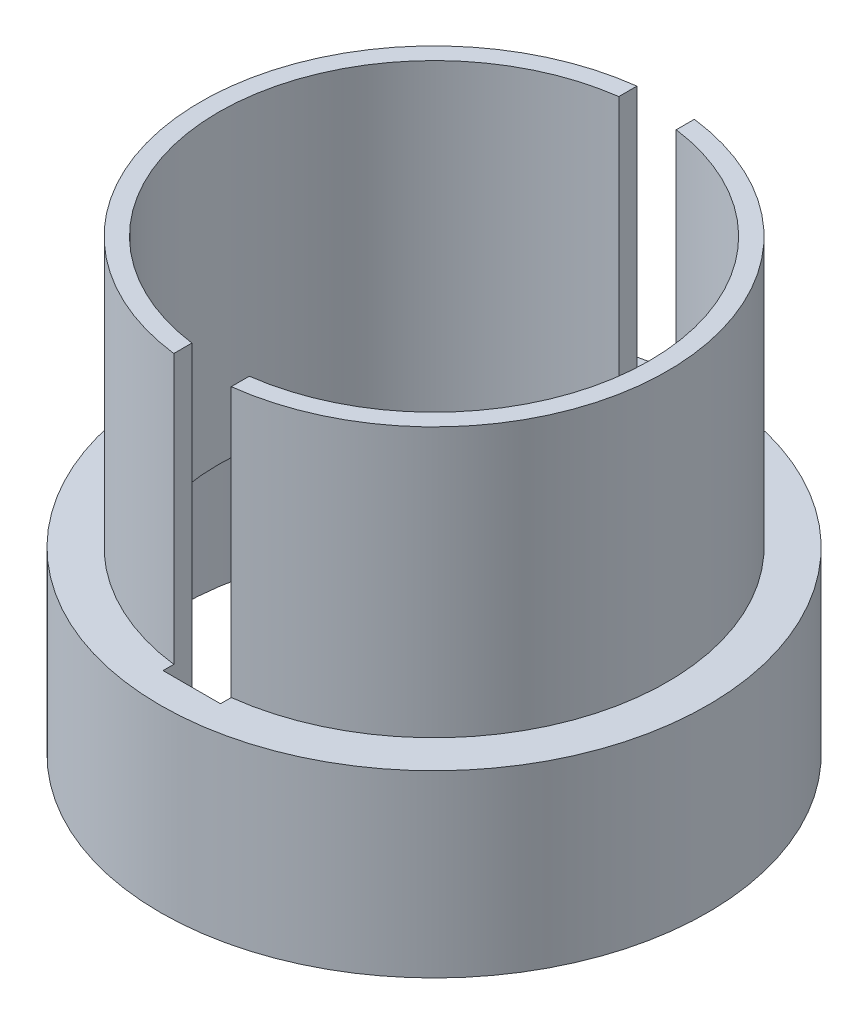
SolidWorks part; units mm, degrees
ref_plane "Front Plane" through (0, 0, 0) normal (0, 0, 1) x (1, 0, 0)
ref_plane "Top Plane" through (0, 0, 0) normal (0, 1, 0) x (1, 0, 0)
ref_plane "Right Plane" through (0, 0, 0) normal (1, 0, 0) x (0, 0, -1)
sketch "Sketch2" plane through (0, 0, 0) normal (0, 1, 0) x (1, 0, 0)
  circle A0 centre (0, 0) radius 15.25
  circle A1 centre (0, 0) radius 14.25
  dimension "D1" = 30.5
  dimension "D2" = 28.5
extrude "Boss-Extrude1" add sketch "Sketch2" along normal blind 10
sketch "Sketch4" plane through (0, 10, 0) normal (0, 1, 0) x (1, 0, 0)
  circle A0 centre (0, 0) radius 14.25
  dimension "D1" = 28.5
extrude "Boss-Extrude2" add sketch "Sketch4" against normal blind 2
sketch "Sketch5" plane through (0, 10, 0) normal (0, 1, 0) x (1, 0, 0)
  circle A0 centre (0, 0) radius 12
  dimension "D1" = 24
extrude "Cut-Extrude1" cut sketch "Sketch5" against normal blind 2
sketch "Sketch6" plane through (0, 10, 0) normal (0, 1, 0) x (1, 0, 0)
  circle A0 centre (0, 0) radius 12
  circle A1 centre (0, 0) radius 13
  dimension "D1" = 24
  dimension "D2" = 26
extrude "Boss-Extrude4" add sketch "Sketch6" along normal blind 15
sketch "Sketch7" plane through (0, 25, 0) normal (0, 1, 0) x (1, 0, 0)
  line L0 (0, 0) -> (0, -13.5)
  line L1 (0, 0) -> (1.6, 0)
  line L2 (0, -13.5) -> (1.6, -13.5)
  line L3 (1.6, 0) -> (1.6, -13.5)
  line L4 (0, 0) -> (0, -13.5)
  line L5 (0, 0) -> (-1.6, 0)
  line L6 (0, -13.5) -> (-1.6, -13.5)
  line L7 (-1.6, 0) -> (-1.6, -13.5)
  line L8 (-1.6, 0) -> (1.6, 0)
  line L9 (-1.6, 0) -> (-1.6, 13.5)
  line L10 (1.6, 0) -> (1.6, 13.5)
  line L11 (-1.6, 13.5) -> (1.6, 13.5)
  circle M5 centre (0, 0) radius 13
  circle M6 centre (0, 0) radius 12
  dimension "D1" = 13.5
  dimension "D2" = 1.6
  dimension "D3" = 1.6
  dimension "D4" = 13.5
extrude "Cut-Extrude3" cut sketch "Sketch7" against normal through all contours L11 L9 L10 M5 | L10 L9 M6 M5 | L3 L0 L2 M5 | L7 L6 L0 M5 | L7 L0 M6 M5 | L3 L0 M6 M5
